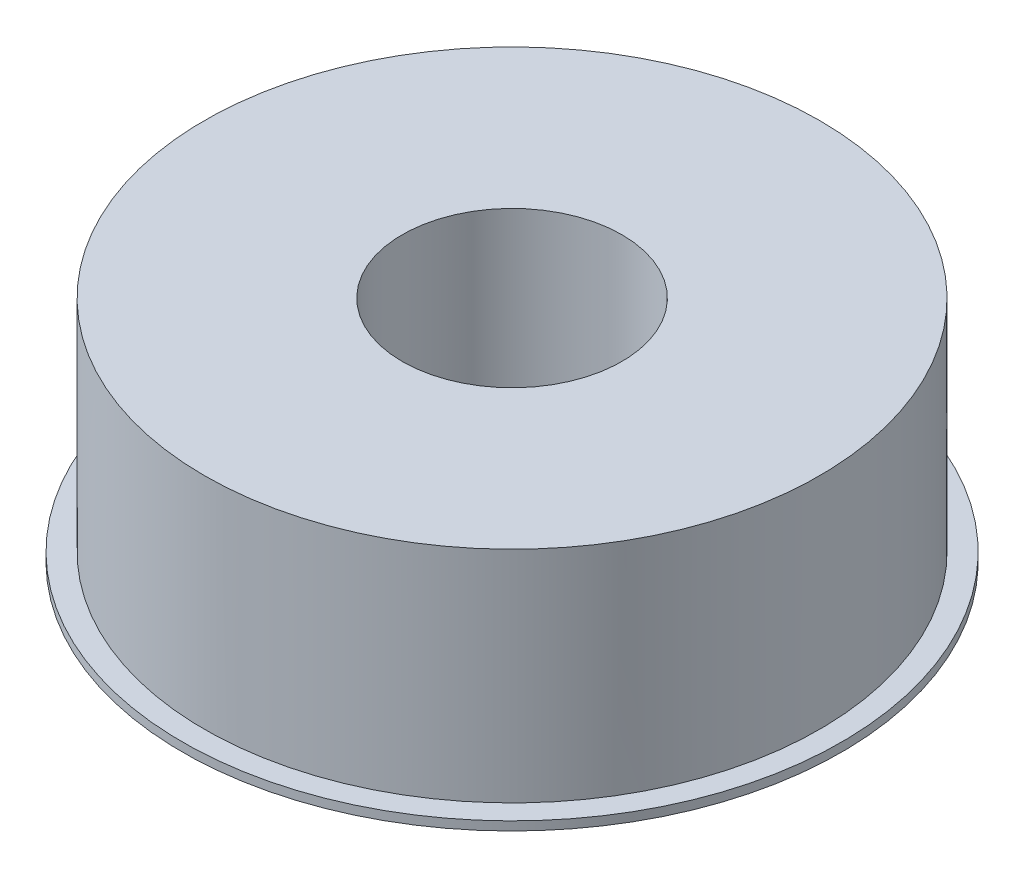
SolidWorks part; units mm, degrees
ref_plane "前视基准面" through (0, 0, 0) normal (0, 0, 1) x (1, 0, 0)
ref_plane "上视基准面" through (0, 0, 0) normal (0, 1, 0) x (1, 0, 0)
ref_plane "右视基准面" through (0, 0, 0) normal (1, 0, 0) x (0, 0, -1)
sketch "草图1" plane through (0, 0, 0) normal (0, 1, 0) x (1, 0, 0)
  circle A0 centre (0, 0) radius 7
extrude "凸台-拉伸1" add sketch "草图1" along normal blind 5
sketch "草图3" plane through (0, 0, 0) normal (0, -1, 0) x (1, 0, 0)
  circle A0 centre (0, 0) radius 7.5
extrude "凸台-拉伸2" add sketch "草图3" along normal blind 0.2
sketch "草图4" plane through (0, 5, 0) normal (0, 1, 0) x (1, 0, 0)
  circle A0 centre (0, 0) radius 2.5
extrude "切除-拉伸2" cut sketch "草图4" against normal blind 10
